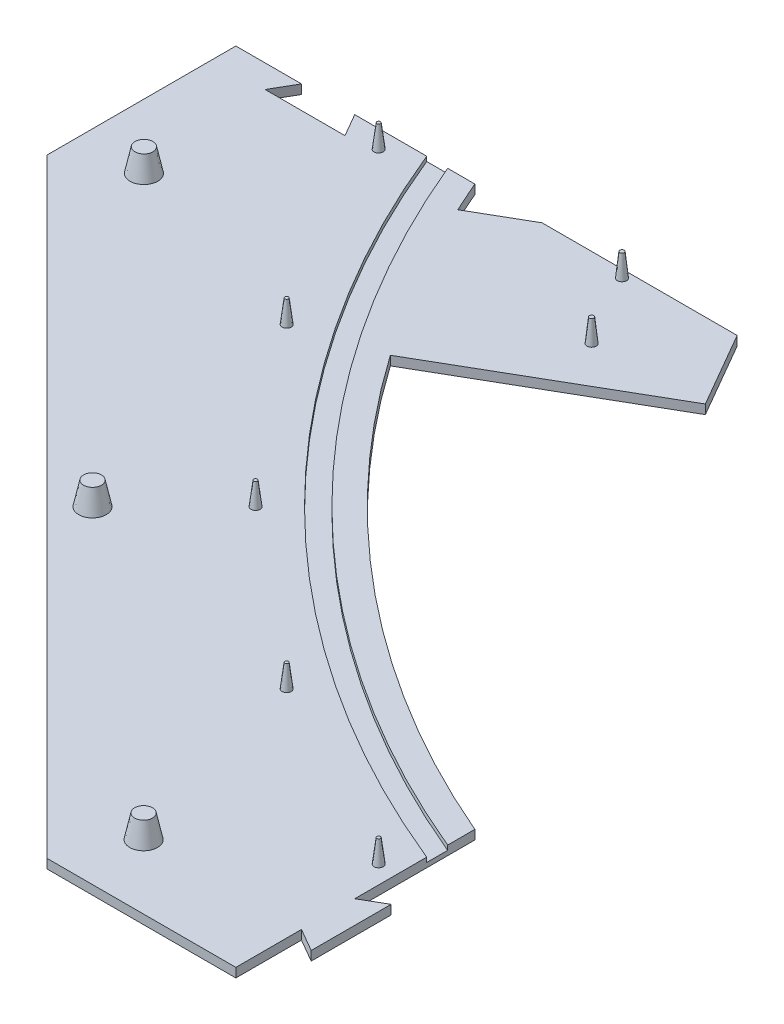
SolidWorks part; units mm, degrees
ref_plane "Front Plane" through (0, 0, 0) normal (0, 0, 1) x (1, 0, 0)
ref_plane "Top Plane" through (0, 0, 0) normal (0, 1, 0) x (1, 0, 0)
ref_plane "Right Plane" through (0, 0, 0) normal (1, 0, 0) x (0, 0, -1)
sketch "Sketch1" plane through (0, 0, 0) normal (0, 1, 0) x (1, 0, 0)
  line L7 (264, 0) -> (264, 131.98)
  line L9 (131.9796, 264) -> (0, 264)
  line L14 (131.9796, 264) -> (264, 131.98)
  line L15 (0, 264) -> (0, 0) construction
  line L16 (264, 109.3524) -> (186.6762, 186.6762) [skipped]
  line L17 (0, 0) -> (264, 0) construction
  line L18 (264, -131.9796) -> (131.98, -264)
  line L19 (-264, 0) -> (-264, -109.3524) [skipped]
  line L20 (-186.6762, 186.6762) -> (-264, 109.3524) [skipped]
  line L21 (-186.6762, -186.6762) -> (-109.3524, -264) [skipped]
  line L22 (0, -264) -> (109.3524, -264) [skipped]
  line L23 (186.6762, -186.6762) -> (264, -109.3524) [skipped]
  line L24 (264, -131.9796) -> (264, 0)
  line L25 (0, -264) -> (131.98, -264)
  line L26 (-131.9796, -264) -> (-264, -131.98)
  line L27 (-131.9796, -264) -> (0, -264)
  line L28 (-264, 0) -> (-264, -131.98)
  line L29 (-264, 131.9796) -> (-131.98, 264)
  line L30 (-264, 131.9796) -> (-264, 0)
  line L31 (0, 264) -> (-131.98, 264)
  arc A0 (264, 0) -> (0, 264) centre (0, 0) ccw construction
  point P33 (0, 0)
  dimension "D1" = 264
  dimension "D2" = 280
  dimension "D3" = 131.98
  dimension "D4" = 4
extrude "baseplate profile" add sketch "Sketch1" against normal blind 2
sketch "Sketch2" plane through (0, 0, 0) normal (0, 1, 0) x (1, 0, 0)
  line L0 (0, -248) -> (0, 248) construction
  circle A0 centre (0, 248) radius 1
  dimension "D2" = 2
  dimension "D1" = 496
extrude "M3 pins" add sketch "Sketch2" along normal blind 5 draft 7
sketch "center line" plane through (0, 0, 0) normal (0, 0, 1) x (1, 0, 0)
  line L0 (0, 0) -> (0, 200) construction
  dimension "D1" = 200
pattern_circular "CirPattern1" count 32 over 360 about axis through (0, 0, 0) along (0, 1, 0) of "M3 pins"
sketch "Sketch4" plane through (0, 0, 0) normal (0, 1, 0) x (1, 0, 0)
  line L0 (0, 0) -> (0, 201) construction
  line L1 (-9, 201) -> (9, 201) construction
  circle A0 centre (9, 201) radius 1
  circle A1 centre (-9, 201) radius 1
  point P5 (0, 201)
  dimension "D3" = 2
  dimension "D4" = 2
  dimension "D1" = 201
  dimension "D2" = 18
extrude "pillar pins" add sketch "Sketch4" along normal blind 5 draft 6
pattern_circular "CirPattern2" count 6 over 360 about axis through (0, 0, 0) along (0, 1, 0) of "pillar pins"
sketch "Sketch5" plane through (0, 0, 0) normal (0, 1, 0) x (1, 0, 0)
  line L0 (-193.0402, 193.0402) -> (193.0402, -193.0402) construction
  line L1 (-131.9796, -264) -> (131.98, -264) construction
  circle A0 centre (-193.0402, 193.0402) radius 3
  dimension "D3" = 6
  dimension "D1" = 546
  dimension "D2" = 45
extrude "M8 hole -1" add sketch "Sketch5" along normal blind 5 draft 12
pattern_circular "M8 -1 pattern" count 4 over 360 about axis through (0, 0, 0) along (0, 1, 0) of "M8 hole -1"
sketch "Sketch6" plane through (0, 0, 0) normal (0, 1, 0) x (1, 0, 0)
  line L0 (0, 0) -> (0, -324.5462) construction
  line L1 (0, 0) -> (-438.1399, 0) construction
  circle A0 centre (-125, -250) radius 3
  dimension "D1" = 6
  dimension "D2" = 125
  dimension "D3" = 250
extrude "M8 -2" add sketch "Sketch6" along normal blind 5 draft 12
pattern_circular "M8 -2 pattern" count 4 over 360 about axis through (0, 0, 0) along (0, 1, 0) of "M8 -2"
pattern_circular "M8 -3" count 2 over 36.9 about axis through (0, 0, 0) along (0, 1, 0) of "M8 -2 pattern", "M8 -2"
sketch "Sketch7" [suppressed] plane through (0, 0, 0) normal (0, 1, 0) x (1, 0, 0)
  line L1 (94.9211, 86.9806) -> (274.9211, 86.9806)
  line L2 (94.9211, 86.9806) -> (94.9211, -93.0194)
  line L3 (94.9211, -93.0194) -> (274.9211, -93.0194)
  line L4 (274.9211, 86.9806) -> (274.9211, -93.0194)
  dimension "D1" = 180
  dimension "D2" = 180
sketch "Sketch8" plane through (0, 0, 0) normal (0, 1, 0) x (1, 0, 0)
  line L0 (0, 0) -> (0, -180) construction
  line L1 (20, -230) -> (-20, -230)
  line L2 (20, -230) -> (20, -180)
  line L3 (20, -180) -> (-20, -180)
  line L4 (-20, -230) -> (-20, -180)
  line L5 (0, 0) -> (115.434, -199.9375)
  line L6 (0, 0) -> (-115.434, -199.9375)
  arc A0 (20, -230) -> (115.434, -199.9375) centre (0, 0) ccw
  arc A1 (-20, -230) -> (-115.434, -199.9375) centre (0, 0) cw
  point P7 (0, -180)
  dimension "D4" = 30
  dimension "D1" = 40
  dimension "D2" = 180
  dimension "D3" = 50
extrude "cut center" cut sketch "Sketch8" against normal through all contours L5 L0 L3 L2 A0 | L0 L6 A1 L4 L3
pattern_circular "CirPattern7" count 6 over 360 about axis through (0, 0, 0) along (0, 1, 0) of "cut center"
sketch "middle piece space " plane through (0, 0, 0) normal (0, 1, 0) x (1, 0, 0)
  line L0 (0, 0) -> (-200, 0) construction
  line L1 (91, 110) -> (-91, 110)
  line L2 (-110, 91) -> (-290, 91)
  line L3 (-110, 91) -> (-110, -91)
  line L4 (-110, -91) -> (-290, -91)
  line L5 (-290, 91) -> (-290, -91)
  line L6 (-110, 91) -> (-290, -91) construction
  line L7 (-110, -91) -> (-290, 91) construction
  line L8 (91, 110) -> (91, 290)
  line L9 (91, 290) -> (-91, 290)
  line L10 (-91, 110) -> (-91, 290)
  line L11 (110, -91) -> (110, 91)
  line L12 (110, -91) -> (290, -91)
  line L13 (290, -91) -> (290, 91)
  line L14 (110, 91) -> (290, 91)
  line L15 (-91, -110) -> (91, -110)
  line L16 (-91, -110) -> (-91, -290)
  line L17 (-91, -290) -> (91, -290)
  line L18 (91, -110) -> (91, -290)
  point P22 (0, 0)
  dimension "D1" = 182
  dimension "D2" = 200
  dimension "D3" = 180
  dimension "D4" = 4
sketch "Sketch11" plane through (0, 0, 0) normal (0, 1, 0) x (1, 0, 0)
  line L0 (-131.9796, -264) -> (131.98, -264) construction
  line L1 (-91, -91) -> (-264, -91)
  line L2 (-91, -91) -> (-91, -264)
  line L3 (-91, -264) -> (-264, -264)
  line L4 (-264, -91) -> (-264, -264)
  line L5 (-264, 131.9796) -> (-264, -131.98) construction
  line L6 (-110, -91) -> (-290, -91) construction
  line L7 (-91, -110) -> (-91, -290) construction
sketch "Sketch13" plane through (0, -2, 0) normal (0, -1, 0) x (1, 0, 0)
  line L1 (295.8455, -414.0765) -> (-305.4926, -414.0765)
  line L2 (295.8455, -414.0765) -> (295.8455, 361.6153)
  line L3 (295.8455, 361.6153) -> (-305.4926, 361.6153)
  line L4 (-305.4926, -414.0765) -> (-305.4926, 361.6153)
  line L5 (-91, 91) -> (-264, 91)
  line L6 (-91, 91) -> (-91, 264)
  line L7 (-91, 264) -> (-264, 264)
  line L8 (-264, 91) -> (-264, 264)
extrude "Cut-Extrude2" cut sketch "Sketch13" against normal blind 10
sketch "Sketch14" plane through (0, 0, 0) normal (0, 1, 0) x (1, 0, 0)
  line L4 (-101, -244) -> (-86, -252.6603)
  line L5 (-86, -252.6603) -> (-86, -235.3397)
  line L6 (-86, -235.3397) -> (-101, -244)
  line L7 (-91, -264) -> (-264, -264) construction
  line L8 (-91, -110) -> (-91, -290) construction
  circle A0 centre (-91, -244) radius 5 construction
  dimension "D2" = 10
  dimension "D3" = 20
extrude "Boss-Extrude1" add sketch "Sketch14" against normal up to surface (2 mm away) up to face at (-177.9038, -2, 143.6681)
sketch "Sketch15" plane through (0, 0, 0) normal (0, 1, 0) x (1, 0, 0)
  line L0 (-110, -91) -> (-290, -91) construction
  line L1 (-252.6603, -96) -> (-235.3397, -96)
  line L2 (-235.3397, -96) -> (-244, -81)
  line L3 (-244, -81) -> (-252.6603, -96)
  line L4 (-264, -91) -> (-264, -264) construction
  circle A0 centre (-244, -91) radius 5 construction
  dimension "D1" = 10
  dimension "D2" = 20
extrude "Cut-Extrude3" cut sketch "Sketch15" against normal through all
sketch "Sketch16" plane through (0, 0, 0) normal (0, 1, 0) x (1, 0, 0)
  circle A0 centre (0, 0) radius 236.3
  circle A1 centre (0, 0) radius 240.5
  dimension "D1" = 472.6
  dimension "D2" = 481
extrude "Cut-Extrude4" cut sketch "Sketch16" against normal blind 1
